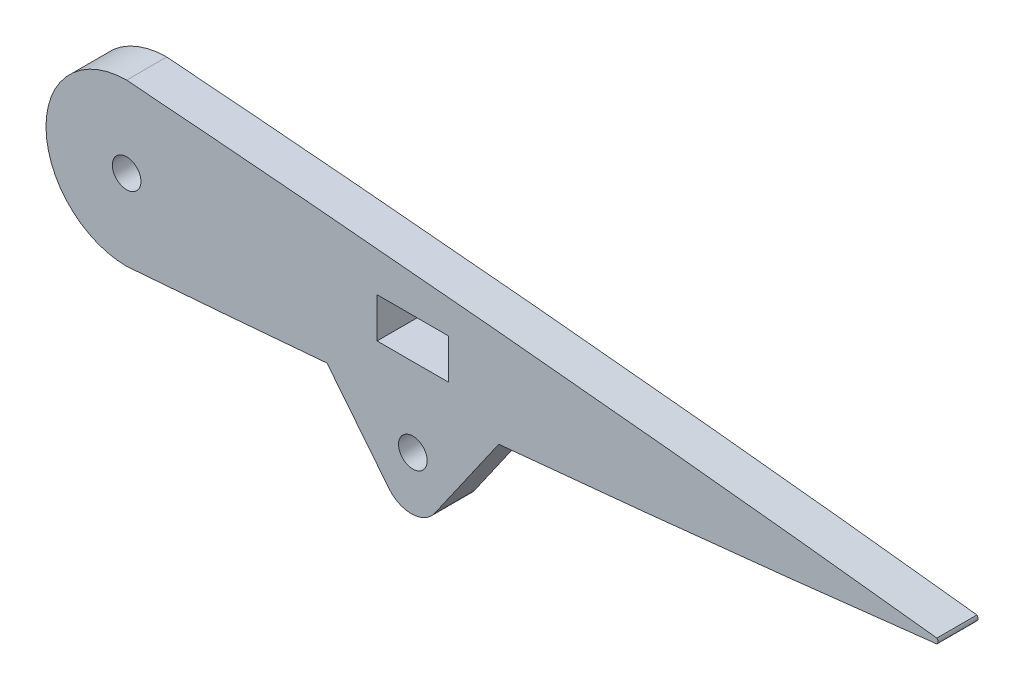
SolidWorks part; units mm, degrees
material "Фанера"
ref_plane "Front Plane" through (0, 0, 0) normal (0, 0, 1) x (1, 0, 0)
ref_plane "Top Plane" through (0, 0, 0) normal (0, 1, 0) x (1, 0, 0)
ref_plane "Right Plane" through (0, 0, 0) normal (1, 0, 0) x (0, 0, -1)
curve "Кривая1"
  spline degree 3 poles (110, 0, 0) (110.0276, -0.2367, 0) (110.0855, -0.7342, 0) (110.5302, -1.4271, 0) (111.1963, -2.0786, 0) (112.1098, -2.7013, 0) (113.2568, -3.2993, 0) (114.6379, -3.8731, 0) (116.2477, -4.4214, 0) (118.0813, -4.9426, 0) (120.1331, -5.4348, 0) (122.3972, -5.8961, 0) (124.8672, -6.3247, 0) (127.537, -6.7187, 0) (130.3997, -7.0764, 0) (133.4488, -7.3965, 0) (136.6771, -7.6776, 0) (140.0777, -7.9187, 0) (143.6433, -8.119, 0) (147.3662, -8.278, 0) (151.2389, -8.3955, 0) (155.2534, -8.4715, 0) (159.4016, -8.5065, 0) (163.6751, -8.501, 0) (168.0653, -8.456, 0) (172.5632, -8.3725, 0) (177.1595, -8.252, 0) (181.8446, -8.096, 0) (186.6087, -7.9062, 0) (191.4413, -7.6846, 0) (196.3316, -7.4331, 0) (201.2684, -7.1538, 0) (206.2396, -6.8489, 0) (211.233, -6.5205, 0) (216.2352, -6.1709, 0) (221.2323, -5.8022, 0) (226.2093, -5.417, 0) (231.1504, -5.0174, 0) (236.0382, -4.6058, 0) (240.8542, -4.1849, 0) (245.5777, -3.7574, 0) (250.1862, -3.3262, 0) (254.6542, -2.8948, 0) (258.9526, -2.4672, 0) (263.0477, -2.0479, 0) (266.899, -1.6426, 0) (270.4558, -1.2586, 0) (273.6512, -0.9053, 0) (276.3854, -0.5964, 0) (278.4526, -0.359, 0) (279.592, -0.2261, 0) (280, -0.1785, 0) knots 0 0 0 0 0.004099 0.008615 0.013935 0.020278 0.027753 0.03641 0.046266 0.05732 0.069559 0.082963 0.097507 0.113164 0.129903 0.14769 0.166492 0.186272 0.206992 0.228612 0.251092 0.274389 0.298458 0.323254 0.348728 0.37483 0.401509 0.42871 0.456376 0.484448 0.512864 0.541558 0.570462 0.599504 0.628607 0.65769 0.686667 0.715445 0.743924 0.771995 0.79954 0.826428 0.852512 0.877624 0.901571 0.924121 0.944989 0.963804 0.980044 0.992855 1 1 1 1
curve "Кривая2"
  spline degree 3 poles (280, 0.1785, 0) (279.592, 0.2261, 0) (278.4526, 0.359, 0) (276.3854, 0.5964, 0) (273.6512, 0.9053, 0) (270.4558, 1.2586, 0) (266.899, 1.6426, 0) (263.0477, 2.0479, 0) (258.9526, 2.4672, 0) (254.6542, 2.8948, 0) (250.1862, 3.3262, 0) (245.5777, 3.7574, 0) (240.8542, 4.1849, 0) (236.0382, 4.6058, 0) (231.1504, 5.0174, 0) (226.2093, 5.417, 0) (221.2323, 5.8022, 0) (216.2352, 6.1709, 0) (211.233, 6.5205, 0) (206.2396, 6.8489, 0) (201.2684, 7.1538, 0) (196.3316, 7.4331, 0) (191.4413, 7.6846, 0) (186.6087, 7.9062, 0) (181.8446, 8.096, 0) (177.1595, 8.252, 0) (172.5632, 8.3725, 0) (168.0653, 8.456, 0) (163.6751, 8.501, 0) (159.4016, 8.5065, 0) (155.2534, 8.4715, 0) (151.2389, 8.3955, 0) (147.3662, 8.278, 0) (143.6433, 8.119, 0) (140.0777, 7.9187, 0) (136.6771, 7.6776, 0) (133.4488, 7.3965, 0) (130.3997, 7.0764, 0) (127.537, 6.7187, 0) (124.8672, 6.3247, 0) (122.3972, 5.8961, 0) (120.1331, 5.4348, 0) (118.0813, 4.9426, 0) (116.2477, 4.4214, 0) (114.6379, 3.8731, 0) (113.2568, 3.2993, 0) (112.1098, 2.7013, 0) (111.1963, 2.0786, 0) (110.5302, 1.4271, 0) (110.0855, 0.7342, 0) (110.0276, 0.2367, 0) (110, 0, 0) knots 0 0 0 0 0.007145 0.019956 0.036196 0.055011 0.075879 0.098429 0.122376 0.147488 0.173572 0.20046 0.228005 0.256076 0.284555 0.313333 0.34231 0.371393 0.400496 0.429538 0.458442 0.487136 0.515552 0.543624 0.57129 0.598491 0.62517 0.651272 0.676746 0.701542 0.725611 0.748908 0.771388 0.793008 0.813728 0.833508 0.85231 0.870097 0.886836 0.902493 0.917037 0.930441 0.94268 0.953734 0.96359 0.972247 0.979722 0.986065 0.991385 0.995901 1 1 1 1
sketch "Эскиз1" plane through (0, 0, 0) normal (0, 0, 1) x (1, 0, 0)
  line L0 (105.1708, 0) -> (280.7263, 0) construction
  line L1 (280.0739, 0) -> (280.0739, 24.3846) construction
  line L2 (110, -5.3315) -> (110, 17.5304) construction
  line L3 (152.5185, 18.8331) -> (152.5185, -21.3473) construction
  line L4 (223.3826, 13.2402) -> (223.3826, -18.4275) construction
  line L5 (217.7476, 6.0581) -> (217.7476, -6.0581)
  line L6 (127.0185, -3) -> (140.0185, -3)
  line L7 (125.0185, -1) -> (125.0185, 1)
  line L8 (127.0185, 3) -> (140.0185, 3)
  line L9 (142.0185, -1) -> (142.0185, 1)
  line L10 (125.0185, -3) -> (142.0185, 3) construction
  line L11 (125.0185, 3) -> (142.0185, -3) construction
  line L12 (165.0185, -4.5) -> (185.0185, -4.5)
  line L13 (163.0185, -2.5) -> (163.0185, 2.5)
  line L14 (165.0185, 4.5) -> (185.0185, 4.5)
  line L15 (187.0185, -2.5) -> (187.0185, 2.5)
  line L16 (163.0185, -4.5) -> (187.0185, 4.5) construction
  line L17 (163.0185, 4.5) -> (187.0185, -4.5) construction
  line L18 (243.3826, 16.1127) -> (243.3826, -19.2013) construction
  line L19 (240.8826, -1.4) -> (245.8826, -1.4)
  line L20 (240.8826, -1.4) -> (240.8826, 1.4)
  line L21 (240.8826, 1.4) -> (245.8826, 1.4)
  line L22 (245.8826, -1.4) -> (245.8826, 1.4)
  line L23 (240.8826, -1.4) -> (245.8826, 1.4) construction
  line L24 (240.8826, 1.4) -> (245.8826, -1.4) construction
  line L25 (237.3826, -4.4873) -> (241.7117, -9.9078)
  line L26 (244.9147, -9.8041) -> (249.3826, -3.4001)
  arc A0 (280, 0.1785) -> (280, -0.1785) centre (279.8215, 0) cw
  circle A1 centre (152.5185, 0) radius 4
  circle A2 centre (197.5185, 0) radius 4
  arc A3 (185.0185, 4.5) -> (187.0185, 2.5) centre (185.0185, 2.5) cw
  arc A4 (185.0185, -4.5) -> (187.0185, -2.5) centre (185.0185, -2.5) ccw
  arc A5 (165.0185, -4.5) -> (163.0185, -2.5) centre (165.0185, -2.5) cw
  arc A6 (163.0185, 2.5) -> (165.0185, 4.5) centre (165.0185, 2.5) cw
  arc A7 (125.0185, 1) -> (127.0185, 3) centre (127.0185, 1) cw
  arc A8 (127.0185, -3) -> (125.0185, -1) centre (127.0185, -1) cw
  arc A9 (140.0185, -3) -> (142.0185, -1) centre (140.0185, -1) ccw
  arc A10 (140.0185, 3) -> (142.0185, 1) centre (140.0185, 1) cw
  arc A11 (223.3826, 5.635) -> (223.3826, -5.635) centre (223.3826, 0) ccw
  circle A12 centre (223.3826, 0) radius 1
  circle A13 centre (243.3826, -6.9031) radius 1
  arc A14 (241.7117, -9.9078) -> (244.9147, -9.8041) centre (243.2745, -8.6597) ccw
  spline S0 degree 3 poles (110, 0) (110.0276, -0.2367) (110.0855, -0.7342) (110.5302, -1.4271) (111.1963, -2.0786) (112.1098, -2.7013) (113.2568, -3.2993) (114.6379, -3.8731) (116.2477, -4.4214) (118.0813, -4.9426) (120.1331, -5.4348) (122.3972, -5.8961) (124.8672, -6.3247) (127.537, -6.7187) (130.3997, -7.0764) (133.4488, -7.3965) (136.6771, -7.6776) (140.0777, -7.9187) (143.6433, -8.119) (147.3662, -8.278) (151.2389, -8.3955) (155.2534, -8.4715) (159.4016, -8.5065) (163.6751, -8.501) (168.0653, -8.456) (172.5632, -8.3725) (177.1595, -8.252) (181.8446, -8.096) (186.6087, -7.9062) (191.4413, -7.6846) (196.3316, -7.4331) (201.2684, -7.1538) (206.2396, -6.8489) (211.233, -6.5205) (216.2352, -6.1709) (221.2323, -5.8022) (226.2093, -5.417) (231.1504, -5.0174) (236.0382, -4.6058) (240.8542, -4.1849) (247.0711, -3.6222) (253.1161, -3.0479) (258.9526, -2.4672) (263.0477, -2.0479) (266.899, -1.6426) (270.4558, -1.2586) (273.6512, -0.9053) (276.3854, -0.5964) (278.4526, -0.359) (279.592, -0.2261) (280, -0.1785) knots 0 0 0 0 0.004099 0.008615 0.013935 0.020278 0.027753 0.03641 0.046266 0.05732 0.069559 0.082963 0.097507 0.113164 0.129903 0.14769 0.166492 0.186272 0.206992 0.228612 0.251092 0.274389 0.298458 0.323254 0.348728 0.37483 0.401509 0.42871 0.456376 0.484448 0.512864 0.541558 0.570462 0.599504 0.628607 0.65769 0.686667 0.715445 0.743924 0.771995 0.79954 0.852512 0.877624 0.901571 0.924121 0.944989 0.963804 0.980044 0.992855 1 1 1 1 construction
  spline S1 degree 3 poles (751.5383, 1938.3796) (440.561, -28.5775) (359.5279, -8.955) (276.3854, 0.5964) (273.6512, 0.9053) (270.4558, 1.2586) (266.899, 1.6426) (263.0477, 2.0479) (258.9526, 2.4672) (253.1161, 3.0479) (247.0711, 3.6222) (240.8542, 4.1849) (236.0382, 4.6058) (231.1504, 5.0174) (226.2093, 5.417) (221.2323, 5.8022) (216.2352, 6.1709) (211.233, 6.5205) (206.2396, 6.8489) (201.2684, 7.1538) (196.3316, 7.4331) (191.4413, 7.6846) (186.6087, 7.9062) (181.8446, 8.096) (177.1595, 8.252) (172.5632, 8.3725) (168.0653, 8.456) (163.6751, 8.501) (159.4016, 8.5065) (155.2534, 8.4715) (151.2389, 8.3955) (147.3662, 8.278) (143.6433, 8.119) (140.0777, 7.9187) (136.6771, 7.6776) (133.4488, 7.3965) (130.3997, 7.0764) (127.537, 6.7187) (124.8672, 6.3247) (122.3972, 5.8961) (120.1331, 5.4348) (118.0813, 4.9426) (116.2477, 4.4214) (114.6379, 3.8731) (113.2568, 3.2993) (112.1098, 2.7013) (111.1963, 2.0786) (110.5302, 1.4271) (105.6546, -6.1694) (164.5198, -33.7739) (-1801.974, 584.7691) knots -1.419625 -1.419625 -1.419625 -1.419625 0.007145 0.019956 0.036196 0.055011 0.075879 0.098429 0.122376 0.147488 0.20046 0.228005 0.256076 0.284555 0.313333 0.34231 0.371393 0.400496 0.429538 0.458442 0.487136 0.515552 0.543624 0.57129 0.598491 0.62517 0.651272 0.676746 0.701542 0.725611 0.748908 0.771388 0.793008 0.813728 0.833508 0.85231 0.870097 0.886836 0.902493 0.917037 0.930441 0.94268 0.953734 0.96359 0.972247 0.979722 0.986065 0.991385 0.995901 1.138851 1.138851 1.138851 1.138851 only from (280, 0.1785) to (110, 0) construction
  spline S2 degree 3 poles (110, 0) (110.0276, -0.2367) (110.0855, -0.7342) (110.5302, -1.4271) (111.1963, -2.0786) (112.1098, -2.7013) (113.2568, -3.2993) (114.6379, -3.8731) (116.2477, -4.4214) (118.0813, -4.9426) (120.1331, -5.4348) (122.3972, -5.8961) (124.8672, -6.3247) (127.537, -6.7187) (130.3997, -7.0764) (133.4488, -7.3965) (136.6771, -7.6776) (140.0777, -7.9187) (143.6433, -8.119) (147.3662, -8.278) (151.2389, -8.3955) (155.2534, -8.4715) (159.4016, -8.5065) (163.6751, -8.501) (168.0653, -8.456) (172.5632, -8.3725) (177.1595, -8.252) (181.8446, -8.096) (186.6087, -7.9062) (191.4413, -7.6846) (196.3316, -7.4331) (201.2684, -7.1538) (206.2396, -6.8489) (211.233, -6.5205) (216.2352, -6.1709) (221.2323, -5.8022) (226.2093, -5.417) (231.1504, -5.0174) (234.8707, -4.7041) (236.9422, -4.5255) (237.3826, -4.4873) knots 0 0 0 0 0.004099 0.008615 0.013935 0.020278 0.027753 0.03641 0.046266 0.05732 0.069559 0.082963 0.097507 0.113164 0.129903 0.14769 0.166492 0.186272 0.206992 0.228612 0.251092 0.274389 0.298458 0.323254 0.348728 0.37483 0.401509 0.42871 0.456376 0.484448 0.512864 0.541558 0.570462 0.599504 0.628607 0.65769 0.686667 0.715445 0.743924 0.751613 0.751613 0.751613 0.751613
  spline S3 degree 3 poles (280, 0.1785) (279.592, 0.2261) (278.4526, 0.359) (276.3854, 0.5964) (273.6512, 0.9053) (270.4558, 1.2586) (266.899, 1.6426) (263.0477, 2.0479) (258.9526, 2.4672) (253.1161, 3.0479) (247.0711, 3.6222) (240.8542, 4.1849) (236.0382, 4.6058) (231.1504, 5.0174) (226.2093, 5.417) (221.2323, 5.8022) (216.2352, 6.1709) (211.233, 6.5205) (206.2396, 6.8489) (201.2684, 7.1538) (196.3316, 7.4331) (191.4413, 7.6846) (186.6087, 7.9062) (181.8446, 8.096) (177.1595, 8.252) (172.5632, 8.3725) (168.0653, 8.456) (163.6751, 8.501) (159.4016, 8.5065) (155.2534, 8.4715) (151.2389, 8.3955) (147.3662, 8.278) (143.6433, 8.119) (140.0777, 7.9187) (136.6771, 7.6776) (133.4488, 7.3965) (130.3997, 7.0764) (127.537, 6.7187) (124.8672, 6.3247) (122.3972, 5.8961) (120.1331, 5.4348) (118.0813, 4.9426) (116.2477, 4.4214) (114.6379, 3.8731) (113.2568, 3.2993) (112.1098, 2.7013) (111.1963, 2.0786) (110.5302, 1.4271) (110.0855, 0.7342) (110.0276, 0.2367) (110, 0) knots 0 0 0 0 0.007145 0.019956 0.036196 0.055011 0.075879 0.098429 0.122376 0.147488 0.20046 0.228005 0.256076 0.284555 0.313333 0.34231 0.371393 0.400496 0.429538 0.458442 0.487136 0.515552 0.543624 0.57129 0.598491 0.62517 0.651272 0.676746 0.701542 0.725611 0.748908 0.771388 0.793008 0.813728 0.833508 0.85231 0.870097 0.886836 0.902493 0.917037 0.930441 0.94268 0.953734 0.96359 0.972247 0.979722 0.986065 0.991385 0.995901 1 1 1 1
  spline S4 degree 3 poles (249.3826, -3.4001) (251.1586, -3.2323) (254.3712, -2.923) (258.9526, -2.4672) (263.0477, -2.0479) (266.899, -1.6426) (270.4558, -1.2586) (273.6512, -0.9053) (276.3854, -0.5964) (278.4526, -0.359) (279.592, -0.2261) (280, -0.1785) knots 0.821481 0.821481 0.821481 0.821481 0.852512 0.877624 0.901571 0.924121 0.944989 0.963804 0.980044 0.992855 1 1 1 1
  point P19 (175.0185, 0)
  point P22 (133.5185, 0)
  point P31 (223.3826, -5.635)
  point P54 (223.3826, 5.635)
  point P55 (223.3826, -5.635)
  point P56 (223.3826, 5.635)
  point P63 (243.3826, 0)
  point P77 (243.3826, -12)
  point P78 (0, 0)
  dimension "D1" = 0.2524
  dimension "D3" = 8
  dimension "D13" = 2
  dimension "D14" = 5.635
  dimension "D15" = 2
  dimension "D22" = 2
  dimension "D23" = 2
  dimension "D2" = 170.0739
  dimension "D4" = 42.5185
  dimension "D5" = 56.6913
  dimension "D6" = 45
  dimension "D7" = 6
  dimension "D8" = 17
  dimension "D9" = 19
  dimension "D10" = 22.5
  dimension "D11" = 9
  dimension "D12" = 24
  dimension "D16" = 2.8
  dimension "D17" = 5
  dimension "D18" = 20
  dimension "D19" = 6
  dimension "D20" = 6
  dimension "D21" = 12
extrude "Бобышка-Вытянуть1" add sketch "Эскиз1" along normal mid plane 2.8 contours A0 S3 A11 S2 A12
equation "\"D4@Эскиз1\"=\"D2@Эскиз1\"/4"
equation "\"D5@Эскиз1\"=\"D2@Эскиз1\"/3"
equation "\"D10@Эскиз1\"=\"D6@Эскиз1\"/2"
